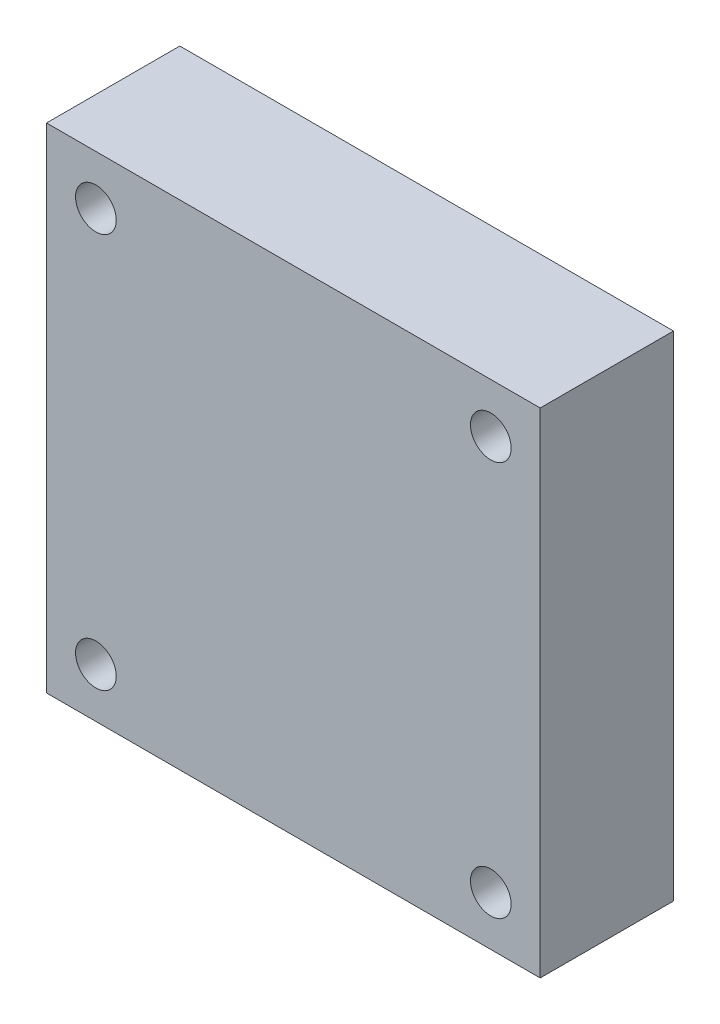
SolidWorks part; units mm, degrees
ref_plane "Front Plane" through (0, 0, 0) normal (0, 0, 1) x (1, 0, 0)
ref_plane "Top Plane" through (0, 0, 0) normal (0, 1, 0) x (1, 0, 0)
ref_plane "Right Plane" through (0, 0, 0) normal (1, 0, 0) x (0, 0, -1)
sketch "Sketch1" plane through (0, 0, 0) normal (0, 0, 1) x (1, 0, 0)
  line L1 (0, 0) -> (40, 0)
  line L2 (0, 0) -> (0, 40)
  line L3 (0, 40) -> (40, 40)
  line L4 (40, 0) -> (40, 40)
  dimension "D1" = 40
  dimension "D2" = 40
extrude "Boss-Extrude1" add sketch "Sketch1" along normal blind 10.8
sketch "Sketch2" plane through (0, 0, 10.8) normal (0, 0, 1) x (1, 0, 0)
  line L0 (0, 20) -> (3.2531, 20) construction
  line L1 (0, 40) -> (0, 0) construction
  line L2 (20, 40) -> (20, 37.3399) construction
  line L3 (40, 40) -> (0, 40) construction
  circle A0 centre (4, 36) radius 1.65
  circle A1 centre (36, 36) radius 1.65
  circle A2 centre (4, 4) radius 1.65
  circle A3 centre (36, 4) radius 1.65
  point P16 (0, 0)
  point P17 (0, 0)
  point P18 (0, 0)
  point P19 (0, 0)
  dimension "D1" = 3.3
  dimension "D2" = 32
  dimension "D3" = 32
  dimension "D4" = 16
  dimension "D5" = 16
extrude "Cut-Extrude1" cut sketch "Sketch2" against normal through all
